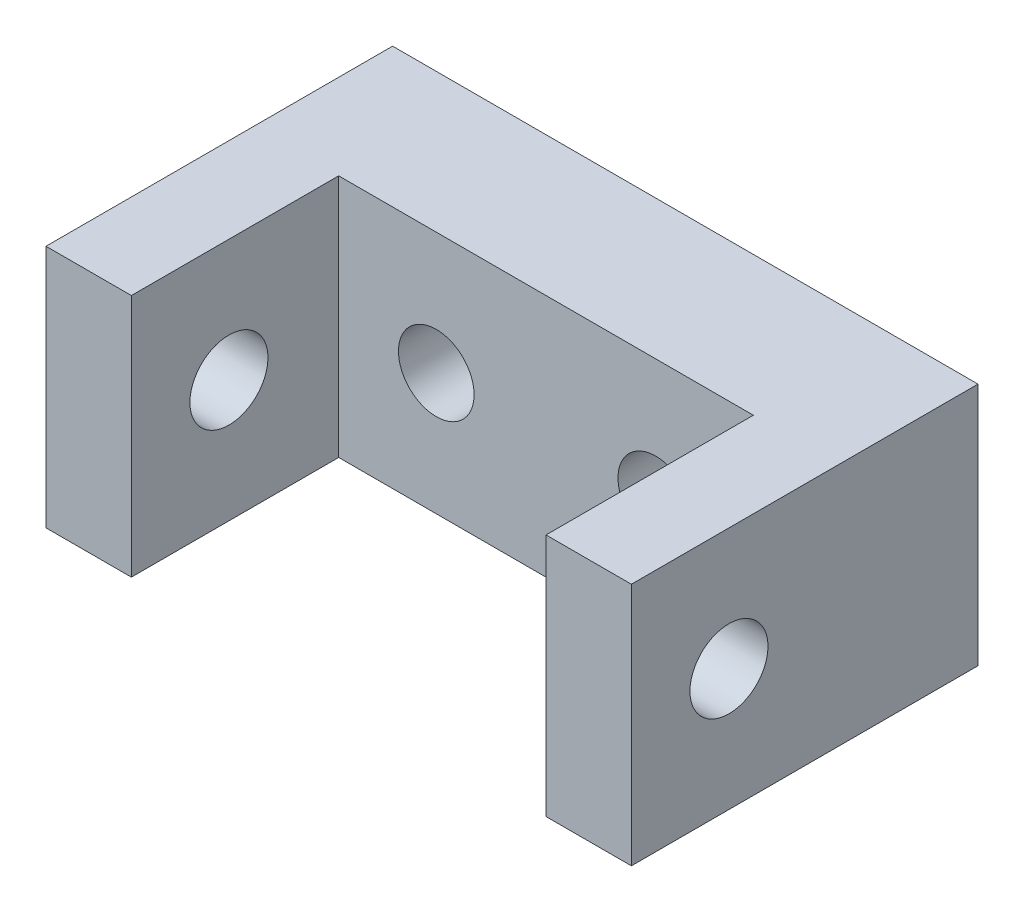
SolidWorks part; units mm, degrees
ref_plane "Alzado" through (0, 0, 0) normal (0, 0, 1) x (1, 0, 0)
ref_plane "Planta" through (0, 0, 0) normal (0, 1, 0) x (1, 0, 0)
ref_plane "Vista lateral" through (0, 0, 0) normal (1, 0, 0) x (0, 0, -1)
sketch "Croquis1" plane through (0, 0, 0) normal (0, 0, 1) x (1, 0, 0)
  line L1 (-12, -5) -> (12, -5)
  line L2 (-12, -5) -> (-12, 5)
  line L3 (-12, 5) -> (12, 5)
  line L4 (12, -5) -> (12, 5)
  line L5 (-12, -5) -> (12, 5) construction
  line L6 (-12, 5) -> (12, -5) construction
  point P0 (0, 0)
  dimension "D1" = 10
  dimension "D2" = 24
extrude "Saliente-Extruir1" add sketch "Croquis1" along normal blind 14.21
sketch "Croquis2" plane through (0, -5, 0) normal (0, -1, 0) x (1, 0, 0)
  line L0 (-12, 14.21) -> (-8.5, 14.21) construction
  line L1 (-12, 14.21) -> (12, 14.21) construction
  line L2 (12, 14.21) -> (8.5, 14.21) construction
  line L3 (-8.5, 14.21) -> (-8.5, 5.71)
  line L4 (8.5, 14.21) -> (8.5, 5.71)
  line L5 (-8.5, 5.71) -> (8.5, 5.71)
  line L6 (-8.5, 14.21) -> (8.5, 14.21)
  dimension "D1" = 3.5
  dimension "D2" = 3.5
  dimension "D3" = 8.5
  dimension "D4" = 8.5
extrude "Cortar-Extruir1" cut sketch "Croquis2" against normal blind 12
sketch "Croquis3" plane through (-12, 0, 0) normal (-1, 0, 0) x (0, 0, 1)
  line L0 (14.21, 5) -> (14.21, -5) construction
  circle A0 centre (10.21, 0) radius 1.6
  dimension "D1" = 3.2
  dimension "D2" = 4
extrude "Cortar-Extruir2" cut sketch "Croquis3" against normal through all
sketch "Croquis4" plane through (0, 0, 5.71) normal (0, 0, 1) x (1, 0, 0)
  circle A0 centre (-4.5, 0) radius 1.55
  circle A1 centre (4.5, 0) radius 1.55
  dimension "D1" = 3.1
  dimension "D2" = 3.1
  dimension "D3" = 4.5
  dimension "D4" = 4.5
extrude "Cortar-Extruir3" cut sketch "Croquis4" against normal blind 12
sketch "Croquis5" [suppressed] plane through (0, 0, 3.5) normal (0, 0, 1) x (1, 0, 0)
  circle A0 centre (-4.5, 0) radius 1.55
  circle A1 centre (4.5, 0) radius 1.55
  dimension "D1" = 3.1
  dimension "D2" = 3.1
  dimension "D3" = 4.5
  dimension "D4" = 4.5
extrude "Cortar-Extruir4" [suppressed] cut sketch "Croquis5" against normal blind 12
